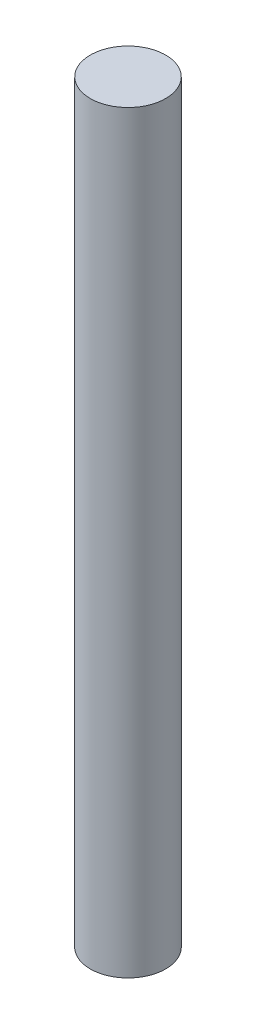
SolidWorks part; units mm, degrees
ref_plane "正面" through (0, 0, 0) normal (0, 0, 1) x (1, 0, 0)
ref_plane "平面" through (0, 0, 0) normal (0, 1, 0) x (1, 0, 0)
ref_plane "右側面" through (0, 0, 0) normal (1, 0, 0) x (0, 0, -1)
sketch "ｽｹｯﾁ1" plane through (0, 0, 0) normal (0, 1, 0) x (1, 0, 0)
  circle A0 centre (0, 0) radius 1.5
  dimension "D1" = 3
extrude "ﾎﾞｽ - 押し出し1" add sketch "ｽｹｯﾁ1" along normal blind 30
